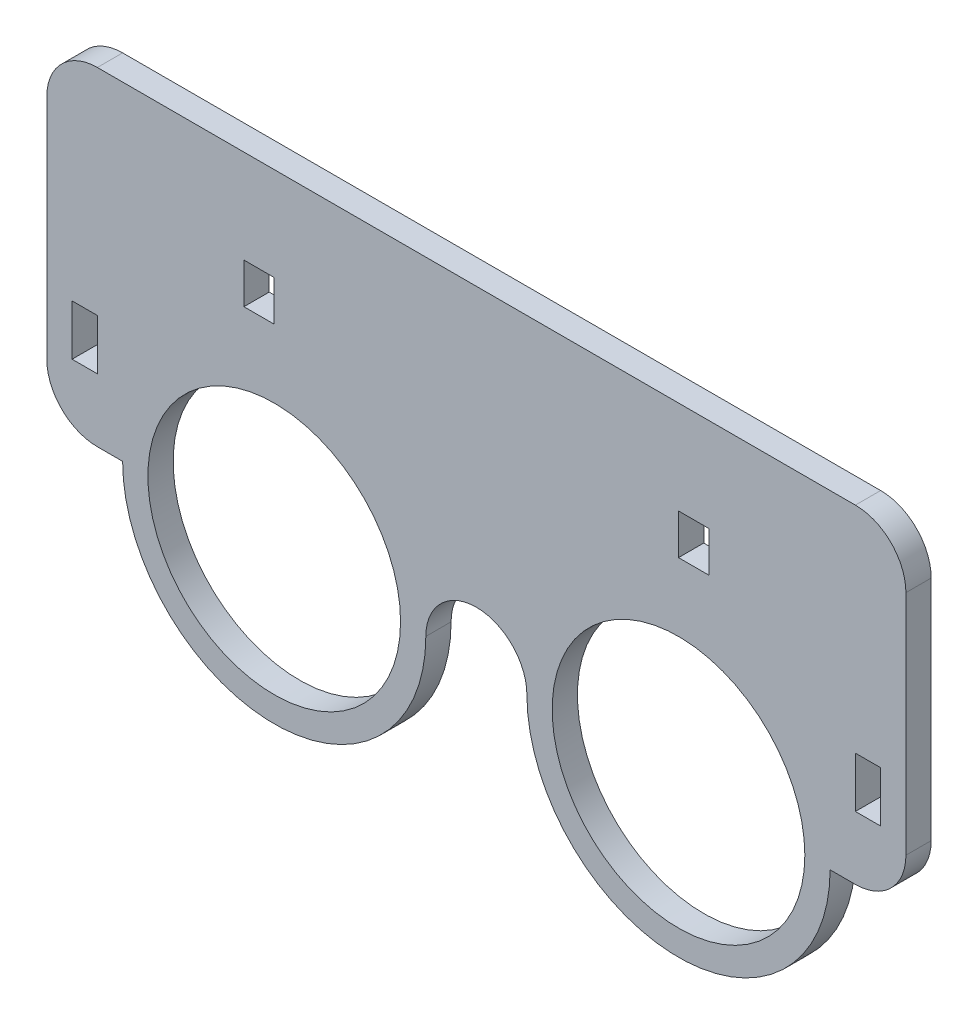
SolidWorks part; units mm, degrees
ref_plane "Front Plane" through (0, 0, 0) normal (0, 0, 1) x (1, 0, 0)
ref_plane "Top Plane" through (0, 0, 0) normal (0, 1, 0) x (1, 0, 0)
ref_plane "Right Plane" through (0, 0, 0) normal (1, 0, 0) x (0, 0, -1)
sketch "Sketch1" plane through (0, 0, 0) normal (0, 0, 1) x (1, 0, 0)
  line L0 (0, 0) -> (0, 99.9751) construction
  line L1 (-65, 60) -> (65, 60) construction
  line L2 (-65, 60) -> (-65, 33.5) construction
  line L3 (-65, 33.5) -> (65, 33.5) construction
  line L4 (65, 60) -> (65, 33.5) construction
  line L5 (-85, 10) -> (-85, 55)
  line L14 (-75, 65) -> (75, 65)
  line L15 (75, 12.5) -> (80, 12.5)
  line L16 (75, 12.5) -> (75, 22.5)
  line L17 (-80, 22.5) -> (-75, 22.5)
  line L18 (-70, 0) -> (-75, 0)
  line L19 (85, 55) -> (85, 10)
  line L20 (80, 12.5) -> (80, 22.5)
  line L21 (-80, 12.5) -> (-75, 12.5)
  line L22 (75, 22.5) -> (80, 22.5)
  line L23 (-80, 22.5) -> (-80, 12.5)
  line L24 (75, 0) -> (70, 0)
  line L25 (-75, 22.5) -> (-75, 12.5)
  line L26 (-46, 38.5) -> (-40, 38.5)
  line L27 (-46, 38.5) -> (-46, 46.5)
  line L28 (-46, 46.5) -> (-40, 46.5)
  line L29 (-40, 38.5) -> (-40, 46.5)
  line L34 (46, 46.5) -> (40, 46.5)
  line L35 (40, 38.5) -> (40, 46.5)
  line L36 (46, 38.5) -> (40, 38.5)
  line L37 (46, 38.5) -> (46, 46.5)
  arc A4 (-70, 0) -> (-10, 0) centre (-40, 0) ccw
  arc A5 (10, 0) -> (-10, 0) centre (0, 0) ccw
  arc A7 (10, 0) -> (70, 0) centre (40, 0) ccw
  arc A8 (75, 65) -> (85, 55) centre (75, 55) cw
  arc A9 (85, 10) -> (75, 0) centre (75, 10) cw
  arc A10 (-85, 10) -> (-75, 0) centre (-75, 10) ccw
  arc A11 (-85, 55) -> (-75, 65) centre (-75, 55) cw
  circle A12 centre (-40, 0) radius 25
  circle A13 centre (40, 0) radius 25
  point P10 (0, 60)
  point P11 (0, 65)
  point P14 (85, 65)
  point P22 (-85, 0)
  point P29 (-85, 65)
  dimension "D1" = 60
  dimension "D2" = 60
  dimension "D3" = 5
  dimension "D5" = 15
  dimension "D6" = 20
  dimension "D7" = 8
  dimension "D18" = 10
  dimension "D19" = 50
  dimension "D20" = 50
  dimension "D4" = 12.5
  dimension "D8" = 65
  dimension "D9" = 170
  dimension "D10" = 12.5
  dimension "D11" = 5
  dimension "D12" = 5
  dimension "D13" = 5
  dimension "D14" = 40
  dimension "D15" = 26.5
  dimension "D16" = 130
  dimension "D17" = 5
  dimension "D21" = 6
  dimension "D22" = 10
  dimension "D23" = 10
  dimension "D24" = 40
  dimension "D25" = 5
extrude "Boss-Extrude1" add sketch "Sketch1" along normal blind 5
